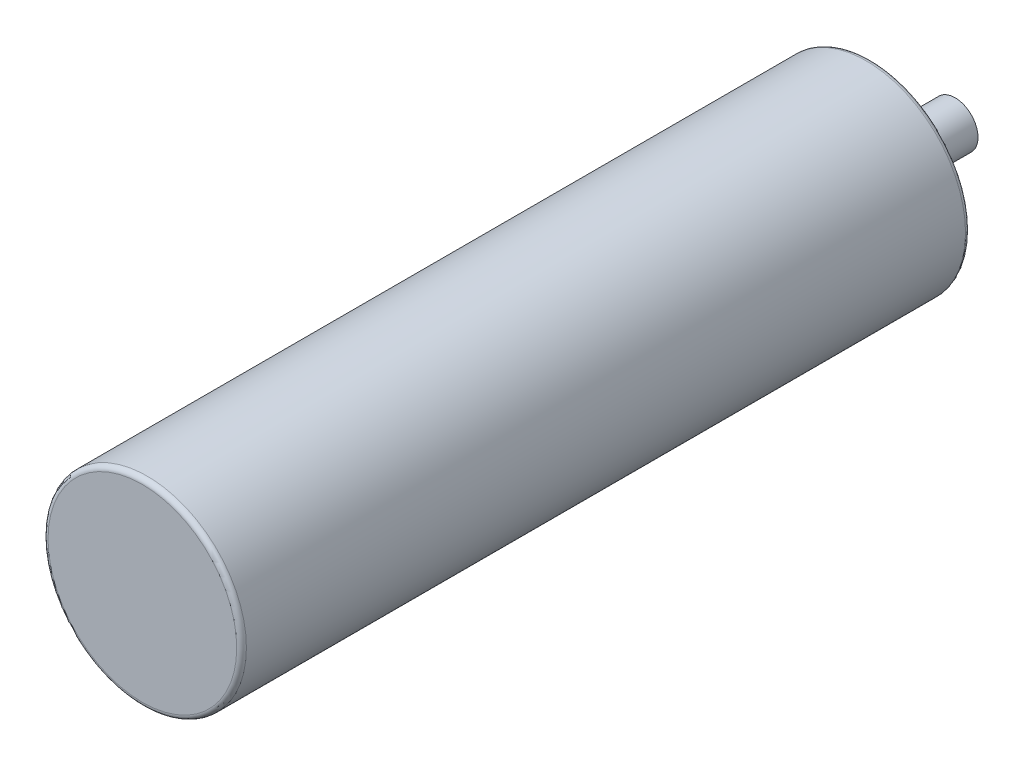
SolidWorks part; units mm, degrees
ref_plane "Front Plane" through (0, 0, 0) normal (0, 0, 1) x (1, 0, 0)
ref_plane "Top Plane" through (0, 0, 0) normal (0, 1, 0) x (1, 0, 0)
ref_plane "Right Plane" through (0, 0, 0) normal (1, 0, 0) x (0, 0, -1)
sketch "Sketch1" plane through (0, 0, 0) normal (0, 0, 1) x (1, 0, 0)
  circle A0 centre (0, 0) radius 26
  dimension "D1" = 52
extrude "body" add sketch "Sketch1" along normal blind 191
sketch "Sketch2" plane through (0, 0, 0) normal (0, 0, -1) x (-1, 0, 0)
  circle A0 centre (0, 0) radius 6
  dimension "D1" = 12
extrude "axle" add sketch "Sketch2" along normal blind 22
sketch "Sketch3" plane through (0, 0, -22) normal (0, 0, -1) x (-1, 0, 0)
  line L0 (-4.4721, -4) -> (4.4721, -4)
  circle A0 centre (0, 0) radius 6 construction
  circle A1 centre (0, 0) radius 6
  circle A2 centre (0, 0) radius 1.016
  point P5 (0, 6)
  circle M2 centre (0, 0) radius 6
  dimension "D1" = 2.032
  dimension "D2" = 10
extrude "flat" cut sketch "Sketch3" against normal blind 15 contours L0 M2 | A2
hole_wizard "M5x0.8 Tapped Hole1" positions "Sketch6" profile "Sketch7" tap size "M5x0.8" standard "ANSI Metric"
sketch "Sketch6" plane through (0, 0, 0) normal (0, 0, -1) x (-1, 0, 0)
  circle A0 centre (0, 0) radius 20
  point P5 (0, -20)
  point P7 (-20, 0)
  point P9 (0, 20)
  point P11 (20, 0)
  dimension "D1" = 40
sketch "Sketch7" plane through (0, -20, 0) normal (1, 0, 0) x (0, 1, 0)
  line L0 (0, 0) -> (0, 33.2618)
  line L1 (0, 33.2618) -> (2.1, 32)
  line L2 (2.1, 32) -> (2.1, 0)
  line L5 (2.1, 0) -> (0, 0)
  line L10 (0, 33.2618) -> (-2.1, 32) construction
  line L11 (0, -6.35) -> (0, 107.95) construction
  dimension "Tap Drill Dia." = 4.2
  dimension "Tap Drill Depth" = 32
  dimension "Drill Angle" = 118
cosmetic thread "Hole Thread1" parameters "D1"=0.254, "D2"=5
cosmetic thread "Hole Thread2" parameters "D1"=0.254, "D2"=5
cosmetic thread "Hole Thread3" parameters "D1"=0.254, "D2"=5
cosmetic thread "Hole Thread4" parameters "D1"=0.254, "D2"=5
fillet "Fillet1" radius 1.27 2 edges at (26, 0, 0) (26, 0, 191)
